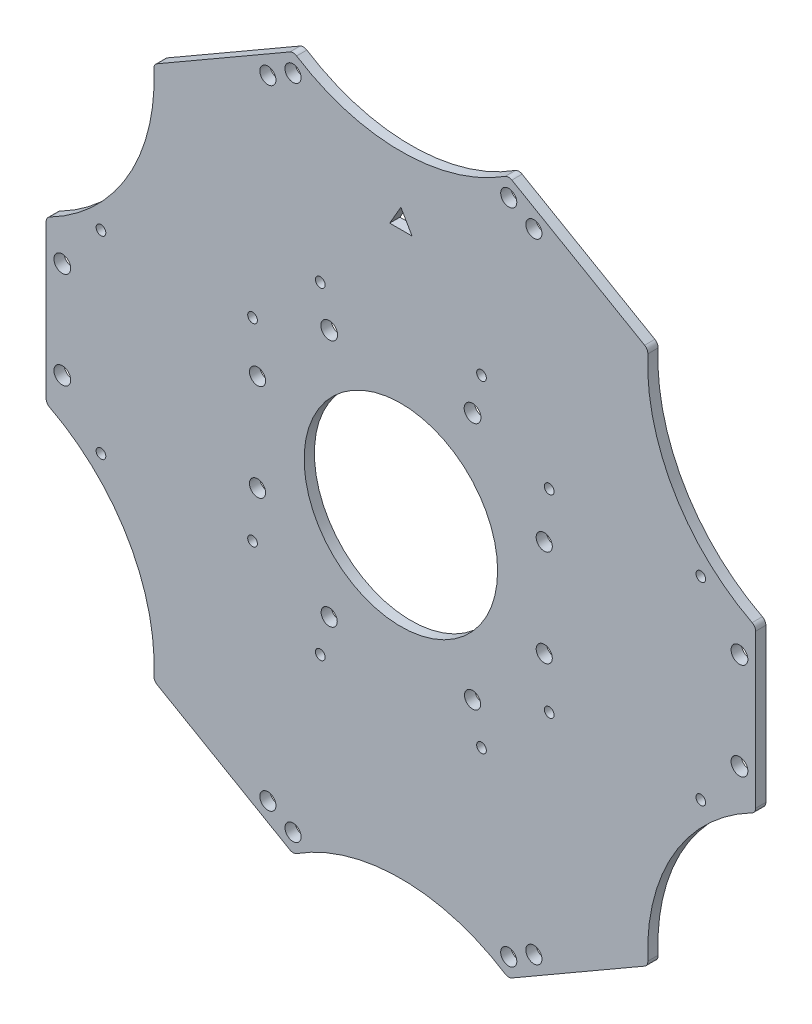
SolidWorks part; units mm, degrees
ref_plane "Front Plane" through (0, 0, 0) normal (0, 0, 1) x (1, 0, 0)
ref_plane "Top Plane" through (0, 0, 0) normal (0, 1, 0) x (1, 0, 0)
ref_plane "Right Plane" through (0, 0, 0) normal (1, 0, 0) x (0, 0, -1)
sketch "Sketch1" plane through (0, 0, 0) normal (0, 0, 1) x (1, 0, 0)
  line L0 (-65, -95.2628) -> (-62.5, -90.9327) construction
  line L1 (-10, 127.0171) -> (-120, 63.5085) construction
  line L2 (-120, 63.5085) -> (-120, -63.5085) construction
  line L3 (-120, -63.5085) -> (-10, -127.0171) construction
  line L4 (-10, -127.0171) -> (100, -63.5085) construction
  line L5 (100, -63.5085) -> (100, 63.5085) construction
  line L6 (100, 63.5085) -> (-10, 127.0171) construction
  line L7 (-54.456, 0) -> (-32.228, -38.5) construction
  line L8 (-32.228, -38.5) -> (12.228, -38.5) construction
  line L9 (12.228, -38.5) -> (34.456, 0) construction
  line L10 (34.456, 0) -> (12.228, 38.5) construction
  line L11 (12.228, 38.5) -> (-32.228, 38.5) construction
  line L12 (-32.228, 38.5) -> (-54.456, 0) construction
  line L13 (-120, 0) -> (-115, 0) construction
  line L14 (-115, -15) -> (-115, 15) construction
  line L15 (100, 0) -> (95, 0) construction
  line L16 (-65, 95.2628) -> (-62.5, 90.9327) construction
  line L17 (45, 95.2628) -> (42.5, 90.9327) construction
  line L18 (45, -95.2628) -> (42.5, -90.9327) construction
  line L19 (95, -15) -> (95, 15) construction
  line L20 (-62.5, -90.9327) -> (-51.2417, -97.4327) construction
  line L21 (42.5, -90.9327) -> (31.2417, -97.4327) construction
  line L22 (-62.5, 90.9327) -> (-51.2417, 97.4327) construction
  line L23 (42.5, 90.9327) -> (31.2417, 97.4327) construction
  line L24 (-51.2417, -97.4327) -> (-43.4474, -101.9327) construction
  line L25 (31.2417, -97.4327) -> (23.4474, -101.9327) construction
  line L26 (-51.2417, 97.4327) -> (-43.4474, 101.9327) construction
  line L27 (31.2417, 97.4327) -> (23.4474, 101.9327) construction
  line L28 (-120, -25) -> (-120, 25)
  line L29 (100, -25) -> (100, 25)
  line L30 (66.6506, 82.7628) -> (23.3494, 107.7628)
  line L31 (-86.6506, 82.7628) -> (-43.3494, 107.7628)
  line L32 (-86.6506, -82.7628) -> (-43.3494, -107.7628)
  line L33 (23.3494, -107.7628) -> (66.6506, -82.7628)
  line L34 (-54.456, 15) -> (-54.456, -15) construction
  line L35 (34.456, 15) -> (34.456, -15) construction
  line L36 (-103, 30) -> (-103, -30) construction
  line L37 (-120, 0) -> (-103, 0) construction
  line L38 (-103, 0) -> (-56, 0) construction
  line L39 (-56, -30) -> (-56, 30) construction
  line L40 (100, 0) -> (83, 0) construction
  line L41 (83, 0) -> (36, 0) construction
  line L42 (36, -30) -> (36, 30) construction
  line L43 (83, -30) -> (83, 30) construction
  line L44 (-35, 50) -> (15, -50) construction
  line L45 (-35, 50) -> (15, 50) construction
  line L46 (-35, 50) -> (-35, -50) construction
  line L47 (-35, -50) -> (15, -50) construction
  line L48 (15, 50) -> (15, -50) construction
  line L49 (-10, 97.6408) -> (-10, 82.6408) construction
  line L50 (-10, 82.6408) -> (-13.4641, 76.6408)
  line L51 (-13.4641, 76.6408) -> (-6.5359, 76.6408)
  line L52 (-6.5359, 76.6408) -> (-10, 82.6408)
  circle A0 centre (-10, 0) radius 110 construction
  circle A1 centre (-10, 0) radius 35 construction
  circle A2 centre (12.228, -38.5) radius 2.5
  circle A3 centre (-54.456, 15) radius 2.5
  circle A4 centre (12.228, 38.5) radius 2.6
  circle A5 centre (-32.228, 38.5) radius 2.6
  circle A6 centre (-54.456, -15) radius 2.5
  circle A7 centre (-32.228, -38.5) radius 2.5
  circle A8 centre (95, 15) radius 2.6
  circle A9 centre (95, -15) radius 2.6
  circle A10 centre (-115, -15) radius 2.6
  circle A11 centre (-115, 15) radius 2.6
  circle A12 centre (31.2417, -97.4327) radius 2.5
  circle A13 centre (23.4474, -101.9327) radius 2.5
  circle A14 centre (-43.4474, -101.9327) radius 2.5
  circle A15 centre (-51.2417, -97.4327) radius 2.5
  circle A16 centre (-51.2417, 97.4327) radius 2.5
  circle A17 centre (-43.4474, 101.9327) radius 2.5
  circle A18 centre (23.4474, 101.9327) radius 2.5
  circle A19 centre (31.2417, 97.4327) radius 2.5
  arc A20 (-120, 25) -> (-86.6506, 82.7628) centre (-146.521, 78.8204) ccw
  arc A21 (-86.6506, -82.7628) -> (-120, -25) centre (-146.521, -78.8204) ccw
  arc A22 (66.6506, 82.7628) -> (100, 25) centre (126.521, 78.8204) ccw
  arc A23 (100, -25) -> (66.6506, -82.7628) centre (126.521, -78.8204) ccw
  arc A24 (23.3494, -107.7628) -> (-43.3494, -107.7628) centre (-10, -157.6408) ccw
  arc A25 (-43.3494, 107.7628) -> (23.3494, 107.7628) centre (-10, 157.6408) ccw
  circle A26 centre (34.456, -15) radius 2.5
  circle A27 centre (34.456, 15) radius 2.5
  circle A28 centre (-103, 30) radius 1.5
  circle A29 centre (-56, 30) radius 1.5
  circle A30 centre (-56, -30) radius 1.5
  circle A31 centre (-103, -30) radius 1.5
  circle A32 centre (36, 30) radius 1.5
  circle A33 centre (36, -30) radius 1.5
  circle A34 centre (83, 30) radius 1.5
  circle A35 centre (83, -30) radius 1.5
  circle A36 centre (-35, 50) radius 1.5
  circle A37 centre (15, 50) radius 1.5
  circle A38 centre (15, -50) radius 1.5
  circle A39 centre (-35, -50) radius 1.5
  circle A40 centre (-10, 78.6408) radius 2 construction
  circle A41 centre (-10, 0) radius 30
  point P38 (95, 0)
  point P39 (-115, 0)
  point P72 (-65, 95.2628)
  point P73 (-120, 0)
  point P74 (-65, -95.2628)
  point P75 (45, -95.2628)
  point P76 (100, 0)
  point P77 (45, 95.2628)
  point P78 (-54.456, 0)
  point P84 (34.456, 0)
  point P98 (-56, 0)
  point P107 (36, 0)
  point P112 (83, 0)
  point P119 (-10, 0)
  dimension "D1" = 220
  dimension "D2" = 70
  dimension "D4" = 5
  dimension "D10" = 120
  dimension "D16" = 3
  dimension "D20" = 4
  dimension "D21" = 60
  dimension "D3" = 5
  dimension "D5" = 30
  dimension "D6" = 13
  dimension "D7" = 9
  dimension "D8" = 127.0171
  dimension "D9" = 50
  dimension "D11" = 60
  dimension "D12" = 47
  dimension "D13" = 17
  dimension "D14" = 17
  dimension "D15" = 47
  dimension "D17" = 50
  dimension "D18" = 100
  dimension "D19" = 15
extrude "Boss-Extrude1" add sketch "Sketch1" along normal blind 3.175
fillet "Fillet1" radius 2 12 edges at (66.6506, 82.7628, 1.5875) (100, 25, 1.5875) (100, -25, 1.5875) (66.6506, -82.7628, 1.5875) (23.3494, -107.7628, 1.5875) (-43.3494, -107.7628, 1.5875) (-120, -25, 1.5875) (-86.6506, -82.7628, 1.5875) (-120, 25, 1.5875) (23.3494, 107.7628, 1.5875) (-43.3494, 107.7628, 1.5875) (-86.6506, 82.7628, 1.5875)
